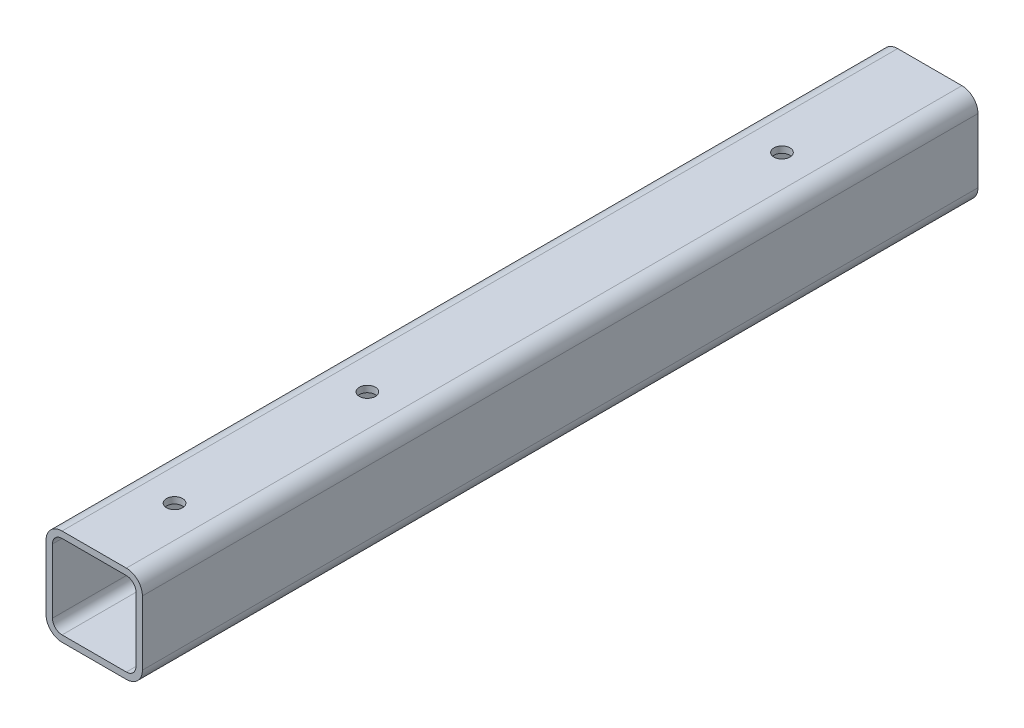
SolidWorks part; units mm, degrees
material "1.0038 (S235JRG2)"
ref_plane "Ebene vorne" through (0, 0, 0) normal (0, 0, 1) x (1, 0, 0)
ref_plane "Ebene oben" through (0, 0, 0) normal (0, 1, 0) x (1, 0, 0)
ref_plane "Ebene rechts" through (0, 0, 0) normal (1, 0, 0) x (0, 0, -1)
sketch "Skizze1" plane through (0, 0, 0) normal (0, 0, 1) x (1, 0, 0)
  line L0 (0, 0) -> (0, 67.8952) construction
  line L1 (-10, 15) -> (10, 15)
  line L2 (0, 0) -> (65.406, 0) construction
  line L3 (15, 10) -> (15, -10)
  line L4 (-15, 10) -> (-15, -10)
  line L5 (-10, -15) -> (10, -15)
  line L6 (-13, 10) -> (-13, -10)
  line L7 (-10, -13) -> (10, -13)
  line L8 (13, 10) -> (13, -10)
  line L9 (-10, 13) -> (10, 13)
  arc A0 (10, 15) -> (15, 10) centre (10, 10) cw
  arc A1 (-10, 15) -> (-15, 10) centre (-10, 10) ccw
  arc A2 (-10, -15) -> (-15, -10) centre (-10, -10) cw
  arc A3 (10, -15) -> (15, -10) centre (10, -10) ccw
  arc A4 (-10, -13) -> (-13, -10) centre (-10, -10) cw
  arc A5 (10, -13) -> (13, -10) centre (10, -10) ccw
  arc A6 (10, 13) -> (13, 10) centre (10, 10) cw
  arc A7 (-10, 13) -> (-13, 10) centre (-10, 10) ccw
  point P12 (15, 0)
  point P13 (0, 15)
  point P19 (-15, 0)
  dimension "D1" = 5
  dimension "D3" = 30
  dimension "D4" = 30
  dimension "D2" = 2
extrude "Aufsatz-Linear austragen1" add sketch "Skizze1" along normal mid plane 260
sketch "Skizze2" plane through (0, -15, 0) normal (0, -1, 0) x (1, 0, 0)
  line L0 (0, 0) -> (0, -143.4738) construction
  line L1 (0, 0) -> (50.9151, 0) construction
  line L2 (-10, -130) -> (10, -130) construction
  line L3 (0, 0) -> (0, 141.9967) construction
  line L4 (-10, 130) -> (10, 130) construction
  circle A0 centre (0, -84) radius 2.5
  circle A2 centre (0, 105) radius 2.5
  circle A3 centre (0, 45) radius 2.5
  dimension "D2" = 5
  dimension "D3" = 25
  dimension "D4" = 60
  dimension "D1" = 46
extrude "Schnitt-Linear austragen1" cut sketch "Skizze2" against normal blind 60
